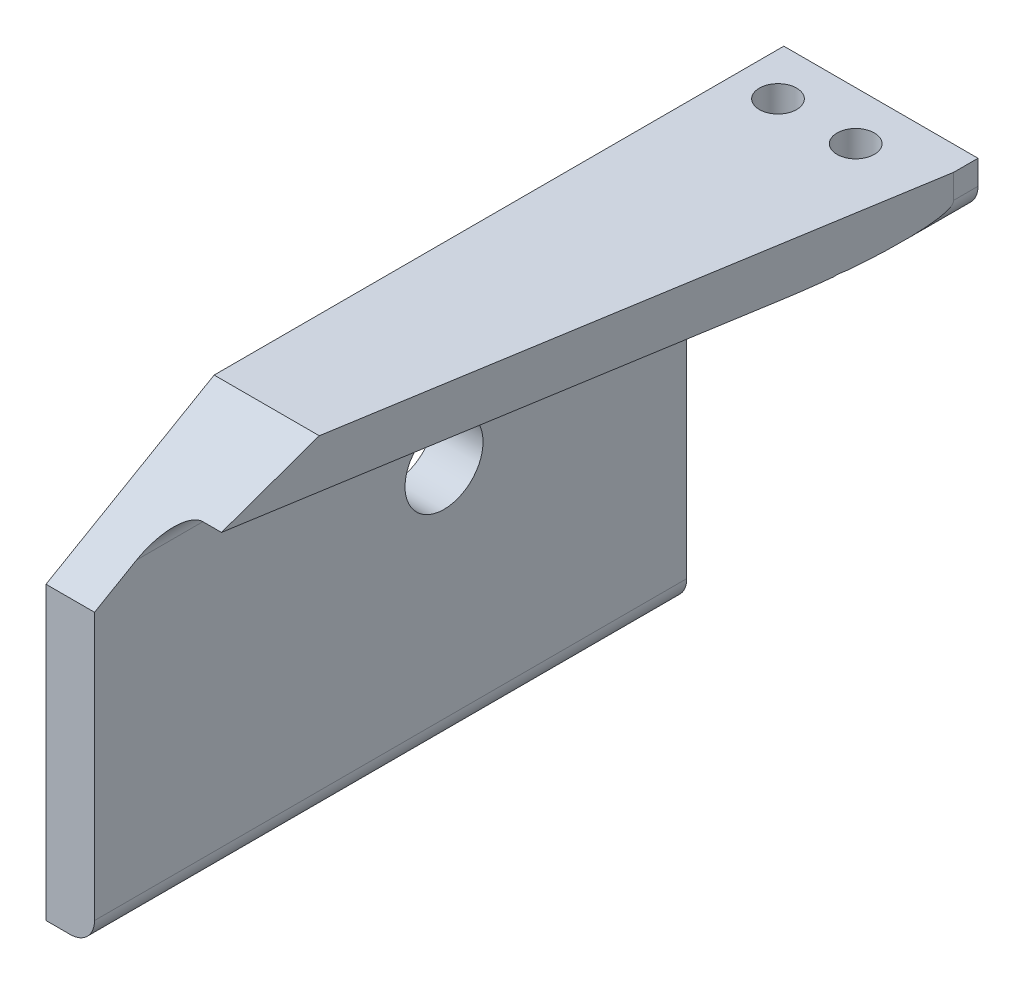
SolidWorks part; units mm, degrees
material "6061-T6 (SS)"
ref_plane "Front Plane" through (0, 0, 0) normal (0, 0, 1) x (1, 0, 0)
ref_plane "Top Plane" through (0, 0, 0) normal (0, 1, 0) x (1, 0, 0)
ref_plane "Right Plane" through (0, 0, 0) normal (1, 0, 0) x (0, 0, -1)
sketch "Sketch1" plane through (0, 0, 0) normal (0, 0, 1) x (1, 0, 0)
  line L0 (0, 0) -> (0, -25.4)
  line L1 (0, -25.4) -> (1.5875, -25.4)
  line L2 (3.175, -23.8125) -> (3.175, -4.7625)
  line L3 (4.7625, -3.175) -> (11.1125, -3.175)
  line L4 (12.7, -1.5875) -> (12.7, 0)
  line L5 (12.7, 0) -> (0, 0)
  arc A0 (1.5875, -25.4) -> (3.175, -23.8125) centre (1.5875, -23.8125) ccw
  arc A1 (11.1125, -3.175) -> (12.7, -1.5875) centre (11.1125, -1.5875) ccw
  arc A2 (3.175, -4.7625) -> (4.7625, -3.175) centre (4.7625, -4.7625) cw
  dimension "D4" = 1.5875
  dimension "D1" = 3.175
  dimension "D2" = 12.7
  dimension "D3" = 25.4
extrude "Boss-Extrude1" add sketch "Sketch1" along normal blind 48.26
sketch "Sketch2" plane through (0, 0, 0) normal (1, 0, 0) x (0, 0, -1)
  line L1 (0, -25.4) -> (-9.525, -25.4)
  line L2 (0, -25.4) -> (0, -3.048)
  line L3 (0, -3.048) -> (-9.525, -3.048)
  line L4 (-9.525, -25.4) -> (-9.525, -3.048)
  line L5 (-48.26, 0) -> (0, 0) construction
  dimension "D1" = 9.525
  dimension "D2" = 3.048
extrude "Cut-Extrude1" cut sketch "Sketch2" along normal through all
sketch "Sketch3" plane through (0, 0, 0) normal (0, 1, 0) x (1, 0, 0)
  line L0 (2.794, -3.175) -> (7.874, -3.175) construction
  line L1 (12.7, 0) -> (0, 0) construction
  line L2 (0, -48.26) -> (0, 0) construction
  circle A0 centre (2.794, -3.175) radius 1.2192
  circle A1 centre (7.874, -3.175) radius 1.2192
  dimension "D1" = 2.4384
  dimension "D2" = 3.175
  dimension "D3" = 2.794
  dimension "D4" = 5.08
extrude "Cut-Extrude2" cut sketch "Sketch3" against normal through all
fillet "Fillet2" radius 1.5875 1 edges at (5.8673, -3.048, 9.525)
sketch "Sketch4" plane through (0, 0, 0) normal (-1, 0, 0) x (0, 0, 1)
  line L0 (19.05, -9.398) -> (31.75, -9.398) construction
  line L2 (4.3942, 0) -> (1.9558, 0) construction
  line L3 (4.3942, 0) -> (1.9558, 0) construction
  line L6 (0, -3.048) -> (7.9375, -3.048) construction
  circle A2 centre (25.4, -9.398) radius 2.5527
  point P8 (3.175, 0)
  point P9 (25.4, -9.398)
  dimension "D2" = 5.1054
  dimension "D1" = 12.7
  dimension "D3" = 6.35
  dimension "D4" = 22.225
extrude "Cut-Extrude3" cut sketch "Sketch4" against normal through all
sketch "Sketch6" plane through (0, 0, 0) normal (0, 1, 0) x (1, 0, 0)
  line L0 (5.08, -48.26) -> (12.7, -1.5875)
  line L1 (12.7, -48.26) -> (0, -48.26) construction
  line L2 (12.7, -48.26) -> (12.7, 0) construction
  line L3 (12.7, -1.5875) -> (12.7, -48.26)
  line L4 (12.7, -48.26) -> (5.08, -48.26)
  circle A0 centre (7.874, -3.175) radius 1.2192 construction
  dimension "D1" = 1.5875
  dimension "D2" = 7.62
extrude "Cut-Extrude4" cut sketch "Sketch6" against normal through all
chamfer "Chamfer2" distance 6.35 angle 60 1 edges at (2.54, 0, 48.26)
